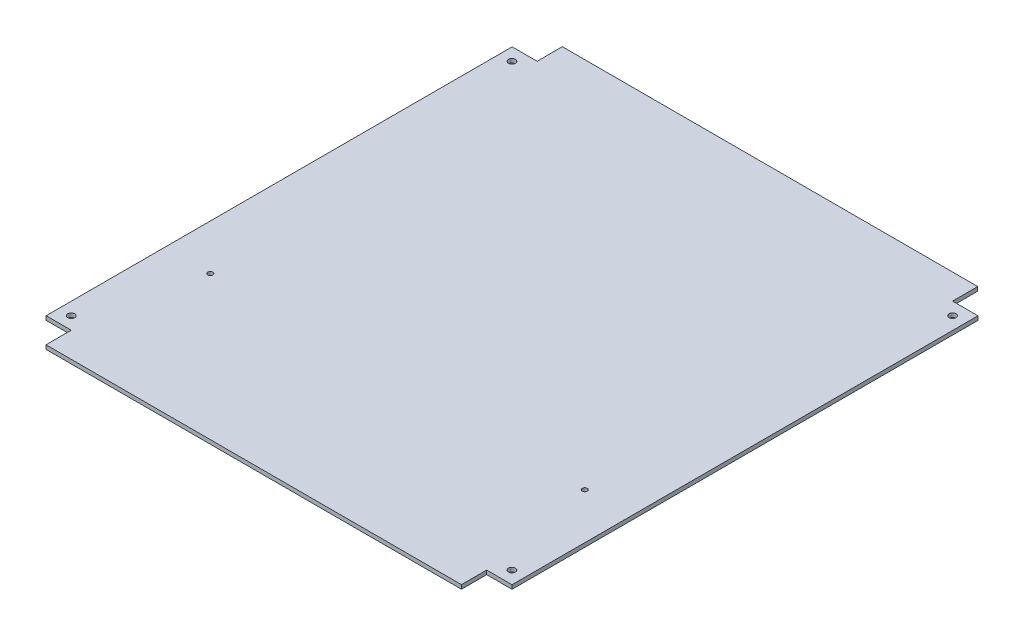
SolidWorks part; units mm, degrees
ref_plane "Front Plane" through (0, 0, 0) normal (0, 0, 1) x (1, 0, 0)
ref_plane "Top Plane" through (0, 0, 0) normal (0, 1, 0) x (1, 0, 0)
ref_plane "Right Plane" through (0, 0, 0) normal (1, 0, 0) x (0, 0, -1)
sketch "Sketch1" plane through (0, 0, 0) normal (0, 1, 0) x (1, 0, 0)
  line L0 (-164.7556, -204.9744) -> (-164.7556, -184.9744)
  line L1 (-164.7556, -184.9744) -> (-184.6556, -184.9744)
  line L2 (-184.6556, -184.9744) -> (-184.5556, 184.6106)
  line L3 (-184.5556, 184.6106) -> (-164.6556, 184.6106)
  line L4 (-164.6556, 184.6106) -> (-164.7556, 204.6106)
  line L5 (-164.7556, 204.6106) -> (164.8194, 204.6106)
  line L6 (164.8194, 204.6106) -> (164.8194, 184.6106)
  line L7 (164.8194, 184.6106) -> (185.0194, 184.6106)
  line L8 (185.0194, 184.6106) -> (184.9294, -184.9744)
  line L9 (184.9294, -184.9744) -> (164.8194, -184.9744)
  line L10 (164.8194, -184.9744) -> (164.8194, -204.9744)
  line L11 (164.8194, -204.9744) -> (-163.3627, -204.9744)
  line L12 (-163.3627, -204.9744) -> (-164.7556, -204.9744)
extrude "Boss-Extrude1" add sketch "Sketch1" along normal blind 3.175
sketch "Sketch2" plane through (0, 3.175, 0) normal (0, 1, 0) x (1, 0, 0)
  line L0 (-184.6556, -184.9744) -> (-164.7556, -184.9744) construction
  line L1 (-164.7556, -184.9744) -> (-164.7556, -204.9744) construction
  line L2 (-184.5556, 184.6106) -> (-184.6556, -184.9744) construction
  line L3 (-164.7556, -204.9744) -> (164.8194, -204.9744) construction
  circle A0 centre (-174.7056, -174.9744) radius 2.75
  circle A5 centre (174.8694, -174.9744) radius 2.75
  circle A6 centre (174.8694, 174.6006) radius 2.75
  circle A7 centre (-174.7056, 174.6006) radius 2.75
  point P0 (-174.7056, -184.9744)
  point P1 (-164.7556, -194.9744)
  point P4 (-184.6556, -184.9744)
  point P7 (-164.7556, -204.9744)
  point P9 (-184.6529, -174.9744)
  point P11 (-154.7556, -204.9744)
  dimension "D1" = 10
  dimension "D2" = 10
  dimension "D5" = 2
  dimension "D6" = 2
extrude "Cut-Extrude1" cut sketch "Sketch2" against normal up to surface (3.175 mm away) up to face at (0.091, 0, 0.1819)
sketch "Sketch3" plane through (0, 3.175, 0) normal (0, 1, 0) x (1, 0, 0)
  circle A0 centre (-148.5031, -90.8984) radius 2
  circle A1 centre (148.5569, -90.8984) radius 2
extrude "Cut-Extrude2" cut sketch "Sketch3" against normal up to surface (3.175 mm away) up to face at (-174.7056, 0, -177.3506)
